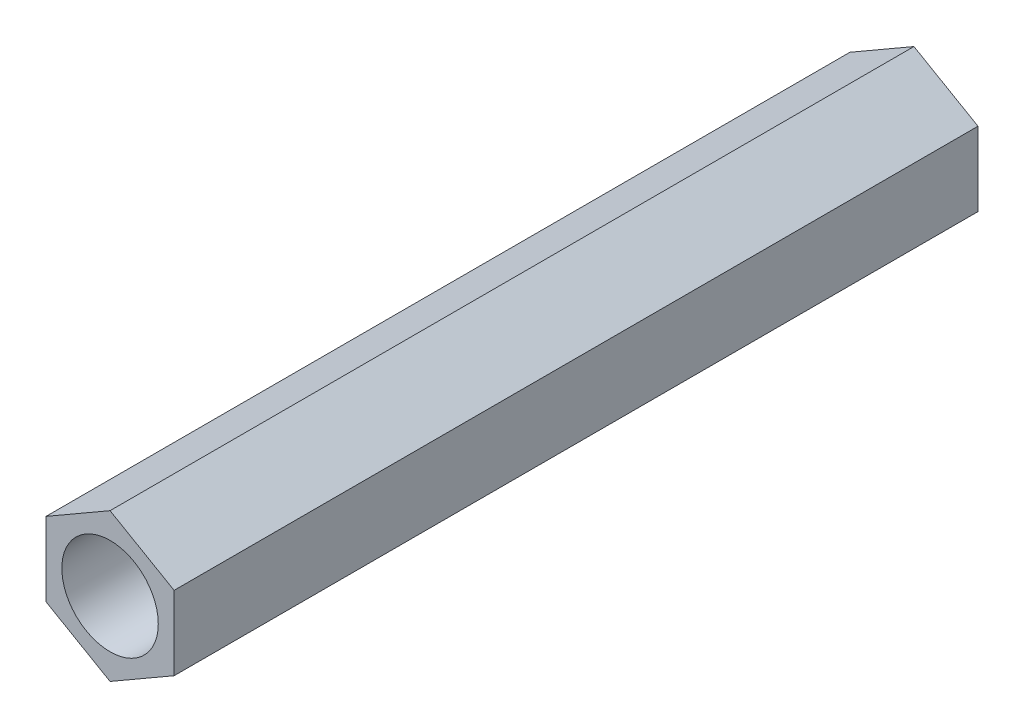
SolidWorks part; units mm, degrees
material "黄铜"
ref_plane "前视基准面" through (0, 0, 0) normal (0, 0, 1) x (1, 0, 0)
ref_plane "上视基准面" through (0, 0, 0) normal (0, 1, 0) x (1, 0, 0)
ref_plane "右视基准面" through (0, 0, 0) normal (1, 0, 0) x (0, 0, -1)
other "Configuration Table"
sketch "草图1" plane through (0, 0, 0) normal (0, 0, 1) x (1, 0, 0)
  line L0 (0, 0) -> (0, 3.2374) construction
  line L1 (0, 2.3) -> (-1.9919, 1.15)
  line L2 (-1.9919, 1.15) -> (-1.9919, -1.15)
  line L3 (-1.9919, -1.15) -> (0, -2.3)
  line L4 (0, -2.3) -> (1.9919, -1.15)
  line L5 (1.9919, -1.15) -> (1.9919, 1.15)
  line L6 (1.9919, 1.15) -> (0, 2.3)
  circle A0 centre (0, 0) radius 1.5
  circle A1 centre (0, 0) radius 1.9919 construction
  dimension "D1" = 3
  dimension "D2" = 4.6
extrude "凸台-拉伸1" add sketch "草图1" along normal blind 25
